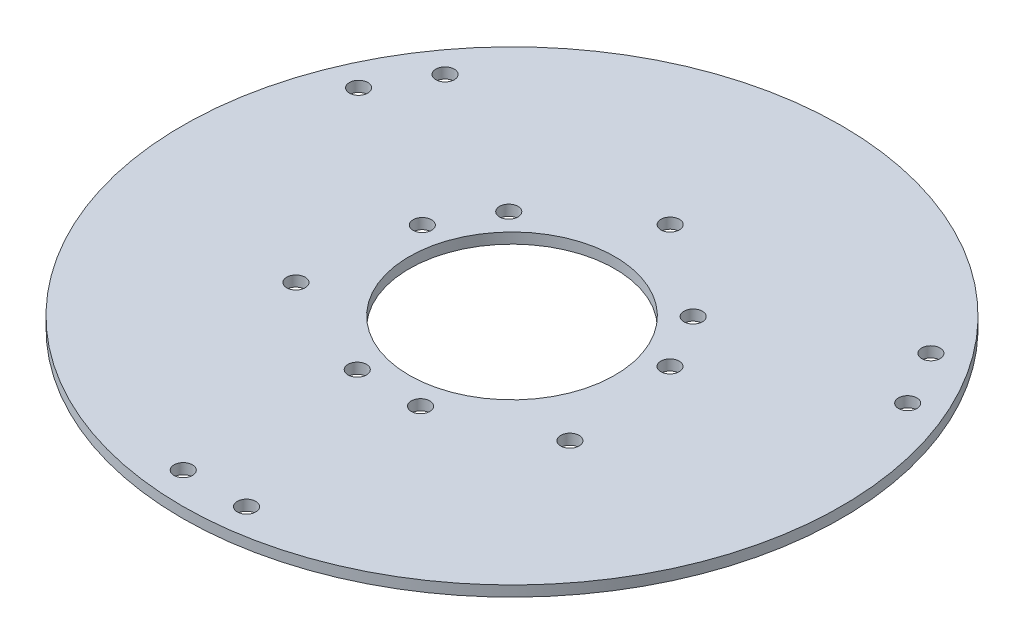
SolidWorks part; units mm, degrees
ref_plane "Front Plane" through (0, 0, 0) normal (0, 0, 1) x (1, 0, 0)
ref_plane "Top Plane" through (0, 0, 0) normal (0, 1, 0) x (1, 0, 0)
ref_plane "Right Plane" through (0, 0, 0) normal (1, 0, 0) x (0, 0, -1)
sketch "Sketch1" plane through (0, 0, 0) normal (0, 1, 0) x (1, 0, 0)
  circle A1 centre (0, 0) radius 62.5
  circle A3 centre (6.1537, -23.5) radius 1.75
  circle A4 centre (-5.8463, -23.5) radius 1.75
  circle A5 centre (6.1537, -56.5) radius 1.75
  circle A6 centre (-5.8463, -56.5) radius 1.75
  circle A7 centre (-46.0073, 33.3131) radius 1.75
  circle A8 centre (-23.4284, 6.4207) radius 1.75
  circle A9 centre (-17.4284, 16.8131) radius 1.75
  circle A10 centre (-52.0073, 22.9207) radius 1.75
  circle A11 centre (51.8536, 23.1869) radius 1.75
  circle A12 centre (17.2748, 17.0793) radius 1.75
  circle A13 centre (23.2748, 6.6869) radius 1.75
  circle A14 centre (45.8536, 33.5793) radius 1.75
  circle A15 centre (0, 0) radius 19.5
  circle A17 centre (0, 30) radius 1.75
  circle A18 centre (25.9808, -15) radius 1.75
  circle A19 centre (-25.9808, -15) radius 1.75
  point P33 (0, 0)
  point P41 (0, 0)
  dimension "D1" = 125
  dimension "D3" = 39
  dimension "D4" = 3.5
  dimension "D5" = 30
  dimension "D2" = 3
  dimension "D6" = 3
extrude "Boss-Extrude1" add sketch "Sketch1" along normal blind 2
